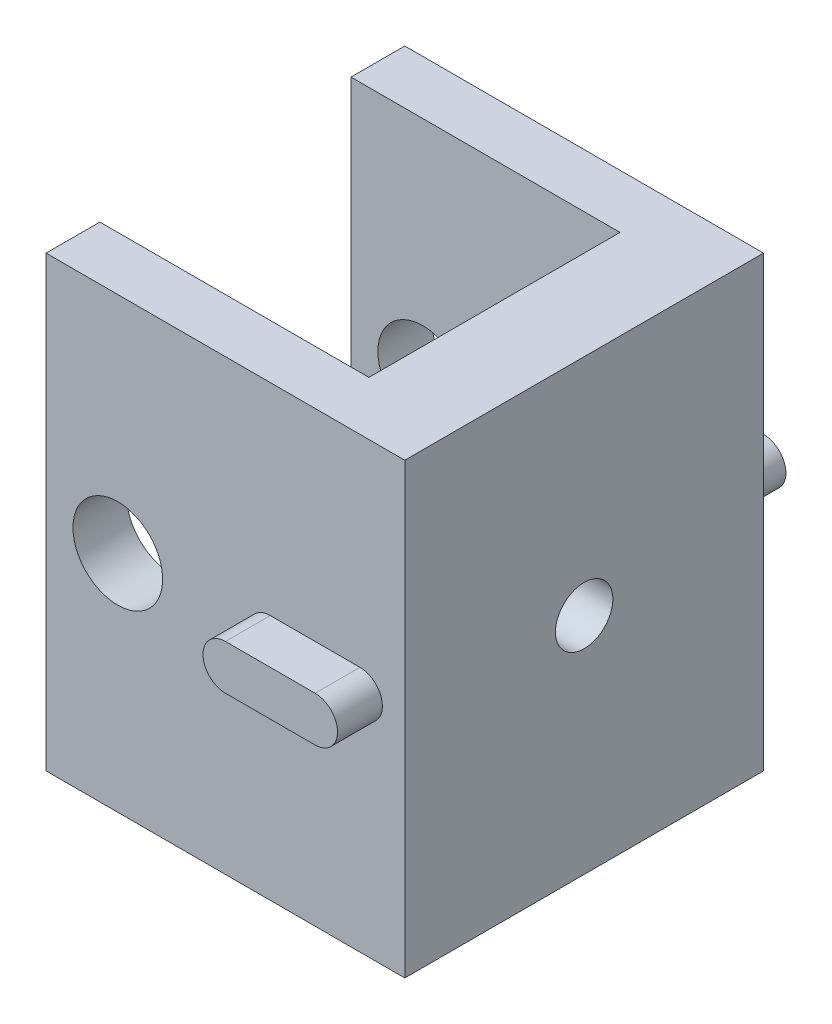
SolidWorks part; units mm, degrees
ref_plane "Спереди" through (0, 0, 0) normal (0, 0, 1) x (1, 0, 0)
ref_plane "Сверху" through (0, 0, 0) normal (0, 1, 0) x (1, 0, 0)
ref_plane "Справа" through (0, 0, 0) normal (1, 0, 0) x (0, 0, -1)
sketch "Эскиз1" plane through (0, 0, 0) normal (0, 1, 0) x (1, 0, 0)
  line L0 (0, 7) -> (0, -7)
  line L1 (0, 7) -> (-15, 7)
  line L2 (-15, 7) -> (-15, 10)
  line L3 (-15, 10) -> (5, 10)
  line L4 (5, 10) -> (5, -10)
  line L5 (5, -10) -> (-15, -10)
  line L6 (-15, -10) -> (-15, -7)
  line L7 (-15, -7) -> (0, -7)
  line L8 (-15, 7) -> (-15, -7) construction
  point P4 (0, 0)
  dimension "D1" = 20
  dimension "D2" = 15
  dimension "D3" = 5
  dimension "D4" = 3
  dimension "D5" = 3
extrude "Бобышка-Вытянуть1" add sketch "Эскиз1" along normal blind 25
sketch "Эскиз2" plane through (0, 0, 0) normal (-1, 0, 0) x (0, 0, 1)
  line L0 (0, 25) -> (0, 0) construction
  line L1 (3, 14.2321) -> (0, 15.9641)
  line L2 (0, 15.9641) -> (-3, 14.2321)
  line L3 (-3, 14.2321) -> (-3, 10.7679)
  line L4 (-3, 10.7679) -> (0, 9.0359)
  line L5 (0, 9.0359) -> (3, 10.7679)
  line L6 (3, 10.7679) -> (3, 14.2321)
  line L7 (-7, 25) -> (7, 25) construction
  circle A0 centre (0, 12.5) radius 3 construction
  point P1 (0, 25)
  point P12 (0, 12.5)
  dimension "D1" = 6
extrude "Вырез-Вытянуть1" cut sketch "Эскиз2" against normal blind 2.5
sketch "Эскиз3" plane through (2.5, 0, 0) normal (-1, 0, 0) x (0, 0, 1)
  line L0 (0, 25) -> (0, 0) construction
  line L1 (-7, 25) -> (7, 25) construction
  circle A0 centre (0, 12.5) radius 1.6
  point P2 (0, 25)
  point P6 (0, 12.5)
  dimension "D1" = 3.2
extrude "Вырез-Вытянуть2" cut sketch "Эскиз3" against normal blind 2.5
sketch "Эскиз4" plane through (0, 0, -10) normal (0, 0, -1) x (-1, 0, 0)
  line L0 (-5, 12.5) -> (15, 12.5) construction
  line L1 (-5, 25) -> (-5, 0) construction
  line L2 (15, 25) -> (15, 0) construction
  line L3 (-2.5, 12.5) -> (2.5, 12.5) construction
  line L4 (-2.5, 13.75) -> (2.5, 13.75)
  line L5 (-2.5, 11.25) -> (2.5, 11.25)
  arc A0 (-2.5, 13.75) -> (-2.5, 11.25) centre (-2.5, 12.5) ccw
  arc A1 (2.5, 11.25) -> (2.5, 13.75) centre (2.5, 12.5) ccw
  point P8 (0, 12.5)
  point P15 (-25.6631, 28.1523)
  dimension "D1" = 2.5
  dimension "D2" = 5
  dimension "D3" = 2.5
extrude "Бобышка-Вытянуть2" add sketch "Эскиз4" along normal blind 2.5
ref_plane "Плоскость1" through (0, 0, 0) normal (0, 0, -1) x (-1, 0, 0)
mirror "Зеркальное отражение1" about plane through (0, 0, 0) normal (0, 0, -1) of "Бобышка-Вытянуть2"
sketch "Эскиз5" plane through (0, 0, -10) normal (0, 0, -1) x (-1, 0, 0)
  line L0 (11, 12.5) -> (-5, 12.5) construction
  line L1 (-5, 25) -> (-5, 0) construction
  line L2 (15, 25) -> (15, 0) construction
  circle A0 centre (11, 12.5) radius 2.5
  point P7 (11, 12.5)
  dimension "D1" = 5
  dimension "D2" = 4
extrude "Вырез-Вытянуть3" cut sketch "Эскиз5" against normal through all
